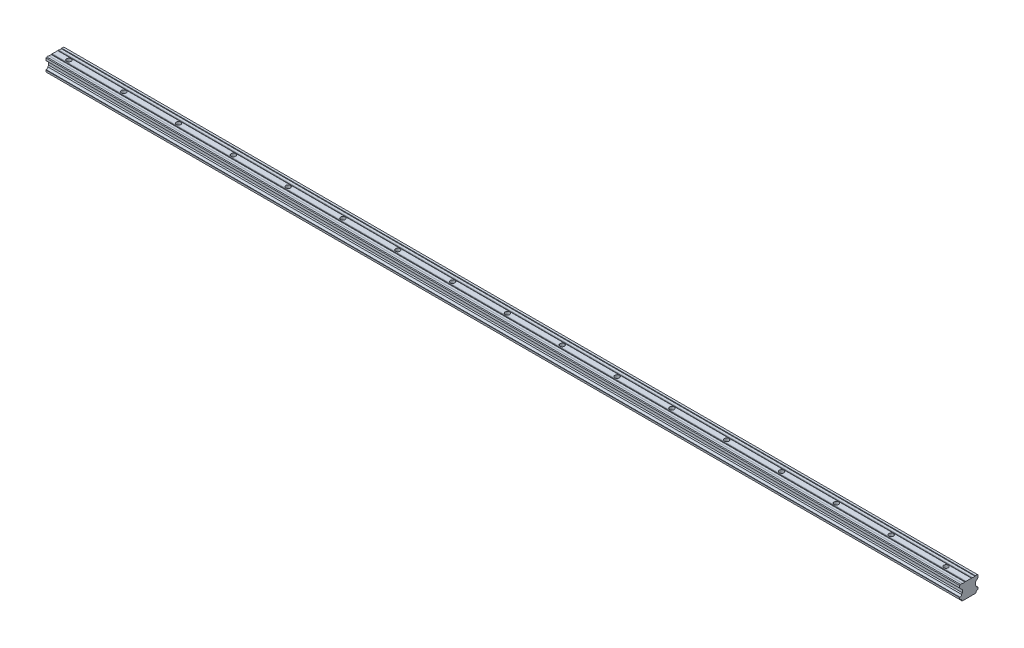
SolidWorks part; units mm, degrees
material "ASTM A36 Steel"
ref_plane "Front Plane" through (0, 0, 0) normal (0, 0, 1) x (1, 0, 0)
ref_plane "Top Plane" through (0, 0, 0) normal (0, 1, 0) x (1, 0, 0)
ref_plane "Right Plane" through (0, 0, 0) normal (1, 0, 0) x (0, 0, -1)
sketch "Sketch1" plane through (0, 0, 0) normal (1, 0, 0) x (0, 0, -1)
  line L0 (-7.9658, -7.694) -> (-7.2663, -8.3935)
  line L1 (-7.2663, -8.3935) -> (7.2663, -8.3935)
  line L2 (7.2663, -8.3935) -> (7.9658, -7.694)
  line L3 (9.7474, -5.9133) -> (10, -5.6608)
  line L4 (10, -5.6608) -> (10, -3.7884)
  line L5 (10, -3.7884) -> (9.7474, -3.5358)
  line L6 (7.9658, -1.7232) -> (7.0051, -0.7626)
  line L7 (7.0051, -0.7626) -> (7.0051, 2.1662)
  line L8 (7.0051, 2.1662) -> (10, 5.1611)
  line L9 (10, 5.1611) -> (10, 7.7124)
  line L10 (10, 7.7124) -> (9.4085, 8.3935)
  line L11 (9.4085, 8.3935) -> (7.133, 8.3935)
  line L12 (7.133, 8.3935) -> (6.7895, 8.05)
  line L13 (6.7895, 8.05) -> (4.2711, 8.05)
  line L14 (4.2711, 8.05) -> (3.9277, 8.3935)
  line L15 (3.9277, 8.3935) -> (3.0613, 8.3935)
  line L16 (3.0613, 8.3935) -> (2.872, 8.2042)
  line L17 (2.872, 8.2042) -> (-2.872, 8.2042)
  line L18 (-2.872, 8.2042) -> (-3.0613, 8.3935)
  line L19 (-3.0613, 8.3935) -> (-3.9277, 8.3935)
  line L20 (-3.9277, 8.3935) -> (-4.2712, 8.05)
  line L21 (-4.2712, 8.05) -> (-6.7895, 8.05)
  line L22 (-6.7895, 8.05) -> (-7.133, 8.3935)
  line L23 (-7.133, 8.3935) -> (-9.3077, 8.3935)
  line L24 (-9.3077, 8.3935) -> (-10, 7.7012)
  line L25 (-10, 7.7012) -> (-10, 5.1611)
  line L26 (-10, 5.1611) -> (-7.0051, 2.1662)
  line L27 (-7.0051, 2.1662) -> (-7.0051, -0.7626)
  line L28 (-7.0051, -0.7626) -> (-7.9658, -1.7232)
  line L29 (-9.7474, -5.9133) -> (-10, -5.6608)
  line L30 (-10, -5.6608) -> (-10, -3.7884)
  line L31 (-10, -3.7884) -> (-9.7474, -3.5358)
  arc A0 (-7.9658, -7.694) -> (-9.7474, -5.9133) centre (-9.7035, -7.6511) ccw
  arc A1 (-9.7474, -3.5358) -> (-7.9658, -1.7232) centre (-9.7025, -1.7981) ccw
  arc A2 (7.9658, -1.7232) -> (9.7474, -3.5358) centre (9.7025, -1.7981) ccw
  arc A3 (9.7474, -5.9133) -> (7.9658, -7.694) centre (9.7035, -7.6511) ccw
extrude "Boss-Extrude1" add sketch "Sketch1" along normal blind 1000
sketch "Croquis1" plane through (0, -8.3935, 0) normal (0, -1, 0) x (-1, 0, 0)
  line L0 (0, 0) -> (-15.5248, 0) construction
  line L1 (0, -7.2663) -> (0, 7.2663) construction
  circle A0 centre (-15, 0) radius 2.5
  dimension "D2" = 5
  dimension "D1" = 15
extrude "Cortar-Extruir1" cut sketch "Croquis1" against normal through all
pattern_linear "MatrizL1" count 17 spacing 60 along (1, 0, 0) of "Cortar-Extruir1"
